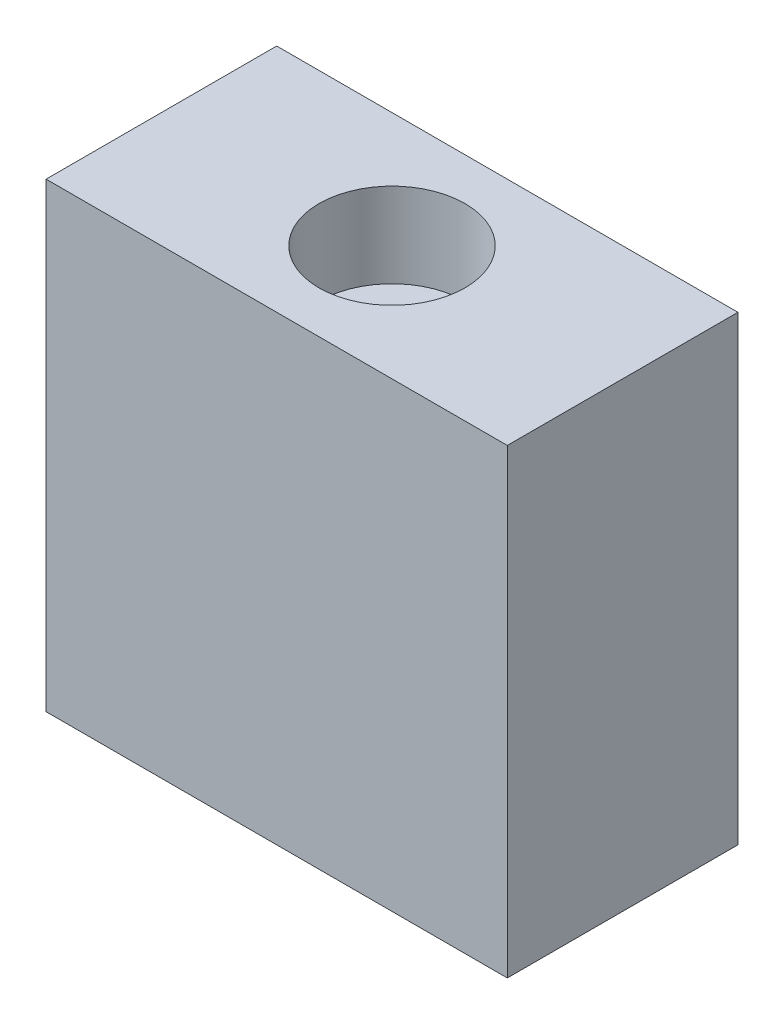
SolidWorks part; units mm, degrees
material "6061 合金"
ref_plane "前视基准面" through (0, 0, 0) normal (0, 0, 1) x (1, 0, 0)
ref_plane "上视基准面" through (0, 0, 0) normal (0, 1, 0) x (1, 0, 0)
ref_plane "右视基准面" through (0, 0, 0) normal (1, 0, 0) x (0, 0, -1)
other "Configuration Table"
sketch "Sketch1" plane through (0, 0, 0) normal (0, 1, 0) x (1, 0, 0)
  line L1 (-15, -7.5) -> (15, -7.5)
  line L2 (-15, -7.5) -> (-15, 7.5)
  line L3 (-15, 7.5) -> (15, 7.5)
  line L4 (15, -7.5) -> (15, 7.5)
extrude "Boss-Extrude1" add sketch "Sketch1" along normal blind 30
sketch "Sketch2" plane through (0, 0, 0) normal (0, 1, 0) x (1, 0, 0)
  circle A0 centre (0, 0) radius 2.75
extrude "Cut-Extrude1" cut sketch "Sketch2" against normal through all and the other way through all
ref_plane "Plane1" through (0, 30, 0) normal (0, 1, 0) x (1, 0, 0)
sketch "Sketch3" plane through (0, 30, 0) normal (0, 1, 0) x (1, 0, 0)
  circle A0 centre (0, 0) radius 4.75
extrude "Cut-Extrude3" cut sketch "Sketch3" against normal blind 5.5
